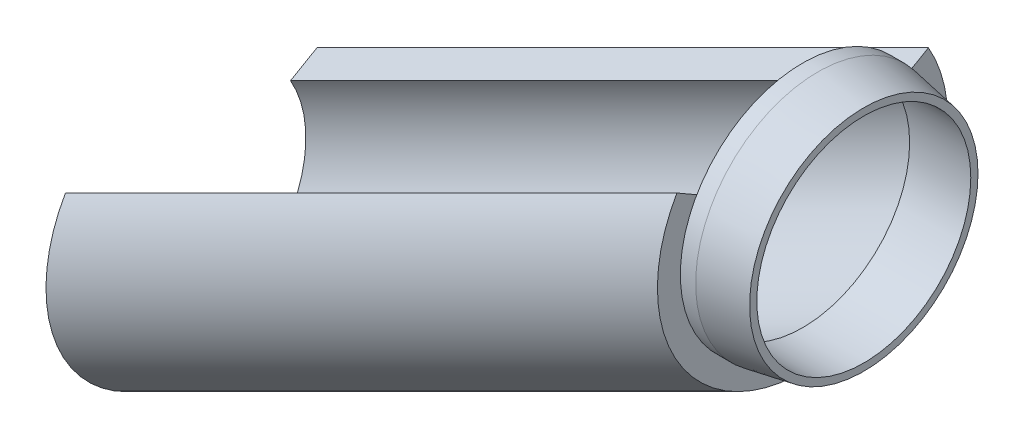
SolidWorks part; units mm, degrees
ref_plane "Front Plane" through (0, 0, 0) normal (0, 0, 1) x (1, 0, 0)
ref_plane "Top Plane" through (0, 0, 0) normal (0, 1, 0) x (1, 0, 0)
ref_plane "Right Plane" through (0, 0, 0) normal (1, 0, 0) x (0, 0, -1)
sketch "Sketch1" plane through (0, 0, 0) normal (1, 0, 0) x (0, 0, -1)
  line L0 (6.4952, 3.75) -> (8.2272, 4.75)
  line L1 (-6.4952, 3.75) -> (-8.2272, 4.75)
  line L2 (0, -7.5) -> (0, -13.6318) construction
  arc A0 (-6.4952, 3.75) -> (6.4952, 3.75) centre (0, 0) ccw
  arc A1 (-8.2272, 4.75) -> (8.2272, 4.75) centre (0, 0) ccw
  circle A2 centre (0, 0) radius 9.5 construction
  circle A3 centre (0, 0) radius 7.5 construction
  dimension "D1" = 2
  dimension "D2" = 120
  dimension "D3" = 120
sketch "Sketch4" plane through (0, 0, 0) normal (0, 0, 1) x (1, 0, 0)
  line L0 (0, 0) -> (-40, -20)
  line L1 (0, -7.5) -> (0, -13.6318) construction
  dimension "D1" = 40
  dimension "D2" = 20
sweep "Sweep1" add profiles "Sketch1" path "Sketch4"
sketch "Sketch5" plane through (0, 0, 0) normal (1, 0, 0) x (0, 0, -1)
  circle A0 centre (0, 0) radius 8
  circle A1 centre (0, 0) radius 7
  dimension "D2" = 16
  dimension "D1" = 1
extrude "Boss-Extrude1" add sketch "Sketch5" along normal blind 4 separate body contours A0 | A1
chamfer "Chamfer1" distance 3 angle 10 1 edges at (4, 0, -8)
